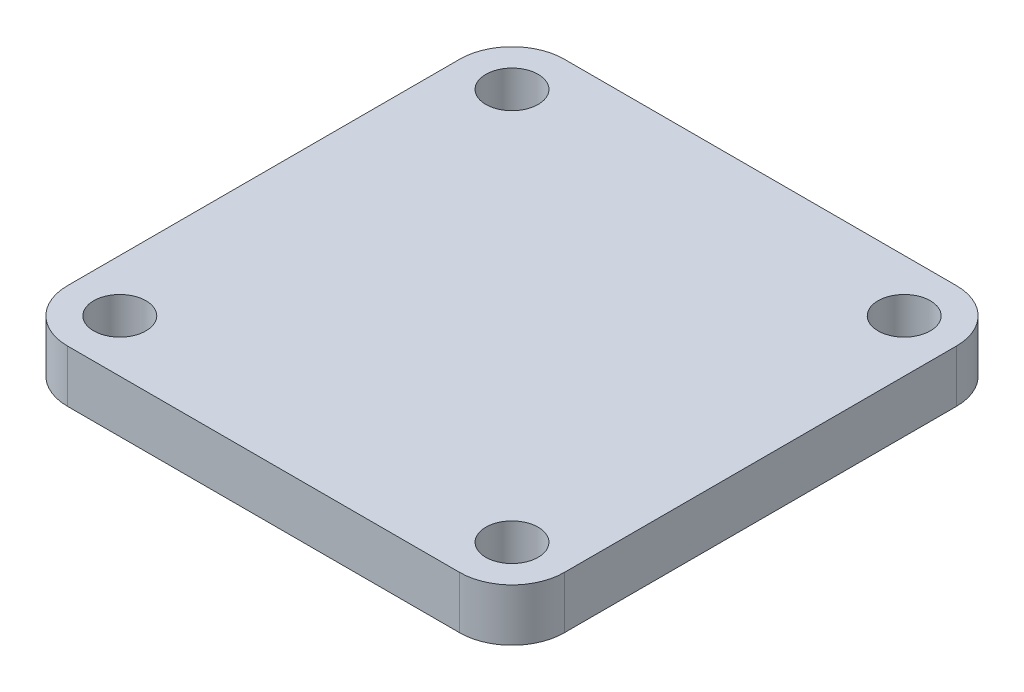
SolidWorks part; units mm, degrees
ref_plane "Спереди" through (0, 0, 0) normal (0, 0, 1) x (1, 0, 0)
ref_plane "Сверху" through (0, 0, 0) normal (0, 1, 0) x (1, 0, 0)
ref_plane "Справа" through (0, 0, 0) normal (1, 0, 0) x (0, 0, -1)
sketch "Эскиз1" plane through (0, 0, 0) normal (0, 1, 0) x (1, 0, 0)
  line L0 (-6.4132, 6.5399) -> (-6.4132, -8.4601) construction
  line L1 (-6.4132, 8.5399) -> (8.5868, 8.5399)
  line L2 (-8.4132, 6.5399) -> (-8.4132, -8.4601)
  line L3 (-6.4132, -10.4601) -> (8.5868, -10.4601)
  line L4 (10.5868, 6.5399) -> (10.5868, -8.4601)
  line L5 (-6.4132, -8.4601) -> (8.5868, -8.4601) construction
  line L6 (8.5868, -8.4601) -> (8.5868, 6.5399) construction
  line L7 (8.5868, 6.5399) -> (-6.4132, 6.5399) construction
  line L8 (-7.4132, 6.5399) -> (-7.4132, -8.4601) construction
  line L9 (-6.4132, -9.4601) -> (8.5868, -9.4601) construction
  line L10 (9.5868, -8.4601) -> (9.5868, 6.5399) construction
  circle A0 centre (-6.4132, 6.5399) radius 1
  circle A1 centre (8.5868, 6.5399) radius 1
  circle A2 centre (8.5868, -8.4601) radius 1
  circle A3 centre (-6.4132, -8.4601) radius 1
  arc A5 (8.5868, -10.4601) -> (10.5868, -8.4601) centre (8.5868, -8.4601) ccw
  arc A6 (-8.4132, -8.4601) -> (-6.4132, -10.4601) centre (-6.4132, -8.4601) ccw
  arc A7 (-6.4132, 8.5399) -> (-8.4132, 6.5399) centre (-6.4132, 6.5399) ccw
  arc A8 (10.5868, 6.5399) -> (8.5868, 8.5399) centre (8.5868, 6.5399) ccw
  dimension "D3" = 2
  dimension "D6" = 15
  dimension "D7" = 15
  dimension "D1" = 19
  dimension "D2" = 19
  dimension "D4" = 2
  dimension "D5" = 2
extrude "Бобышка-Вытянуть2" add sketch "Эскиз1" along normal blind 2
